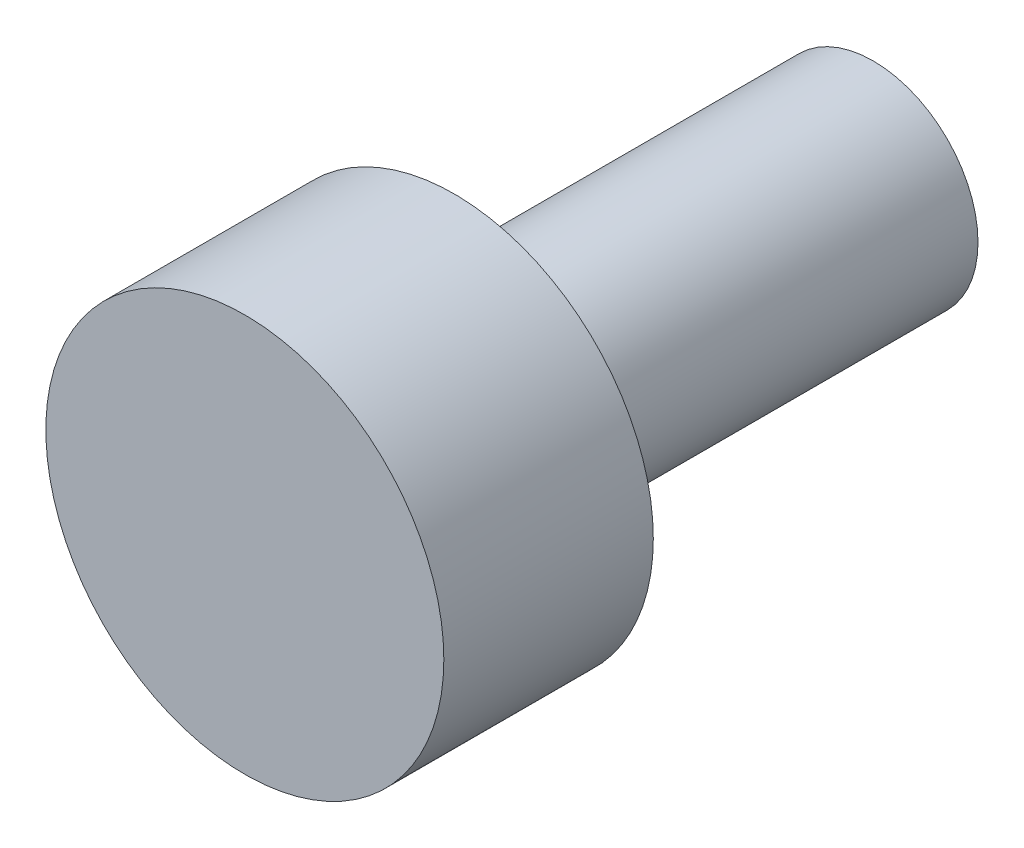
SolidWorks part; units mm, degrees
ref_plane "Front Plane" through (0, 0, 0) normal (0, 0, 1) x (1, 0, 0)
ref_plane "Top Plane" through (0, 0, 0) normal (0, 1, 0) x (1, 0, 0)
ref_plane "Right Plane" through (0, 0, 0) normal (1, 0, 0) x (0, 0, -1)
sketch "Sketch1" plane through (0, 0, 0) normal (0, 0, 1) x (1, 0, 0)
  circle A0 centre (0, 0) radius 1.5
  dimension "D1" = 3
extrude "Boss-Extrude1" add sketch "Sketch1" along normal blind 6
sketch "Sketch2" plane through (0, 0, 6) normal (0, 0, 1) x (1, 0, 0)
  circle A0 centre (0, 0) radius 2.85
  dimension "D1" = 5.7
extrude "Boss-Extrude2" add sketch "Sketch2" along normal blind 3
